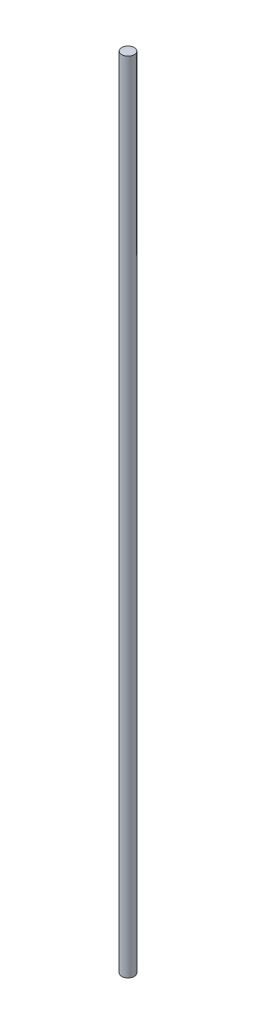
SolidWorks part; units mm, degrees
material "Plain Carbon Steel"
ref_plane "Front Plane" through (0, 0, 0) normal (0, 0, 1) x (1, 0, 0)
ref_plane "Top Plane" through (0, 0, 0) normal (0, 1, 0) x (1, 0, 0)
ref_plane "Right Plane" through (0, 0, 0) normal (1, 0, 0) x (0, 0, -1)
sketch "Sketch1" plane through (0, 0, 0) normal (0, 1, 0) x (1, 0, 0)
  circle A0 centre (0, 0) radius 1.9844
  dimension "D1" = 3.9688
extrude "Boss-Extrude1" add sketch "Sketch1" along normal blind 254
sketch "Sketch3" plane through (0, 0, 0) normal (1, 0, 0) x (0, 0, -1)
  line L0 (0, 253.5381) -> (0, 131.7111)
